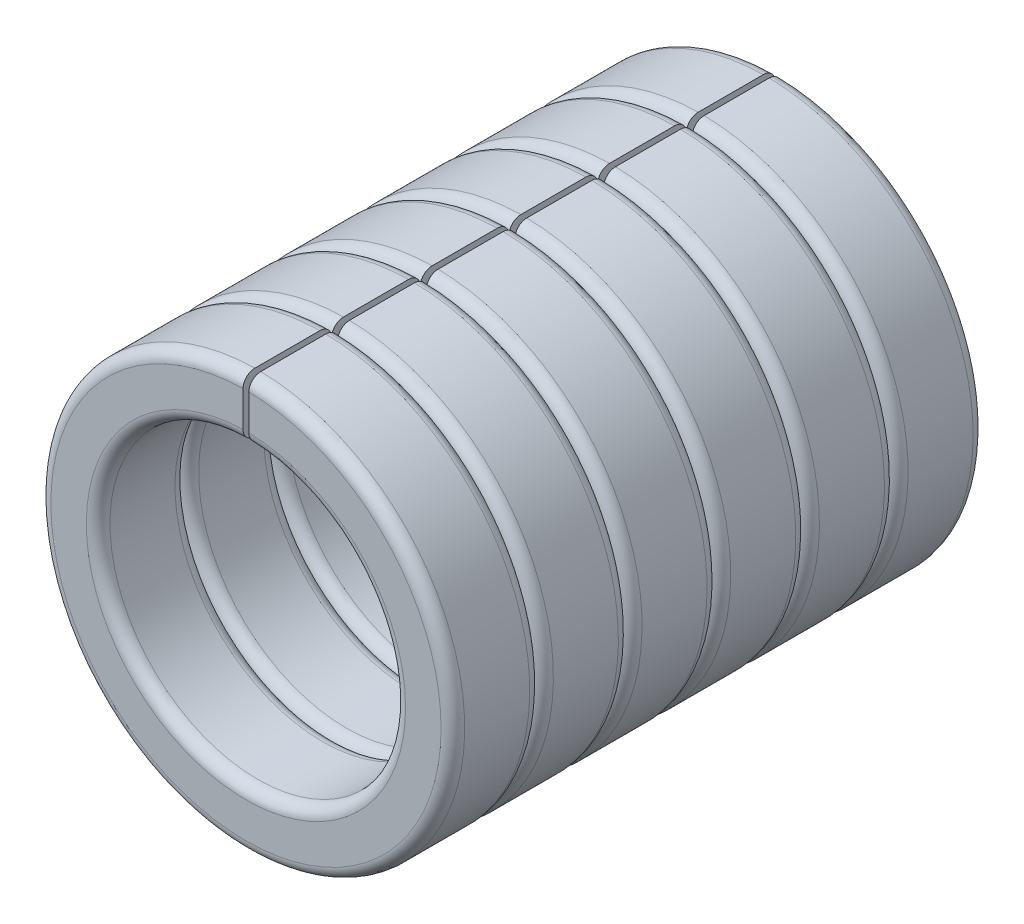
SolidWorks part; units mm, degrees
material "VITON"
ref_plane "Front Plane" through (0, 0, 0) normal (0, 0, 1) x (1, 0, 0)
ref_plane "Top Plane" through (0, 0, 0) normal (0, 1, 0) x (1, 0, 0)
ref_plane "Right Plane" through (0, 0, 0) normal (1, 0, 0) x (0, 0, -1)
sketch "Sketch2" plane through (0, 0, 0) normal (0, 1, 0) x (1, 0, 0)
  line L0 (0, 0) -> (0, 55.4551) construction
  line L1 (-27, 0.7) -> (-33, 0.7)
  line L2 (-25, 2.7) -> (-25, 13.7)
  line L3 (-27, 15.7) -> (-33, 15.7)
  line L4 (-35, 2.7) -> (-35, 13.7)
  line L5 (-25, 0.7) -> (-35, 15.7) construction
  line L6 (-25, 15.7) -> (-35, 0.7) construction
  arc A0 (-25, 13.7) -> (-27, 15.7) centre (-27, 13.7) ccw
  arc A1 (-27, 0.7) -> (-25, 2.7) centre (-27, 2.7) ccw
  arc A2 (-33, 0.7) -> (-35, 2.7) centre (-33, 2.7) cw
  arc A3 (-33, 15.7) -> (-35, 13.7) centre (-33, 13.7) ccw
  point P0 (-30, 8.2)
  dimension "D4" = 2
  dimension "D1" = 10
  dimension "D2" = 15
  dimension "D3" = 25
revolve "Revolve1" add sketch "Sketch2" angle 360 about L0
sketch "Sketch3" plane through (0, 0, -0.7) normal (0, 0, 1) x (1, 0, 0)
  line L1 (0.5, -0.9445) -> (-0.5, -0.9445)
  line L2 (0.5, -0.9445) -> (0.5, 75.1933)
  line L3 (0.5, 75.1933) -> (-0.5, 75.1933)
  line L4 (-0.5, -0.9445) -> (-0.5, 75.1933)
  line L5 (0.5, -0.9445) -> (-0.5, 75.1933) construction
  line L6 (0.5, 75.1933) -> (-0.5, -0.9445) construction
  point P0 (0, 37.1244)
  dimension "D1" = 1
extrude "Cut-Extrude1" cut sketch "Sketch3" against normal blind 20
pattern_linear "LPattern1" count 7 spacing 15 along (0, 0, -1) skipping (6, 0) of "Revolve1", "Cut-Extrude1"
